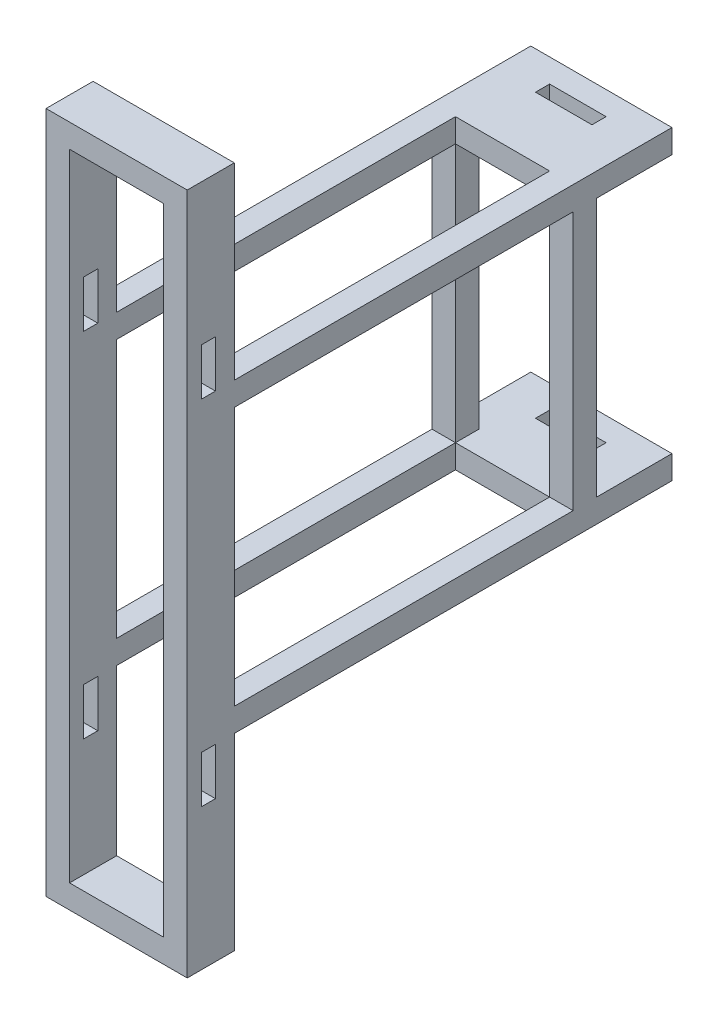
SolidWorks part; units mm, degrees
ref_plane "Front Plane" through (0, 0, 0) normal (0, 0, 1) x (1, 0, 0)
ref_plane "Top Plane" through (0, 0, 0) normal (0, 1, 0) x (1, 0, 0)
ref_plane "Right Plane" through (0, 0, 0) normal (1, 0, 0) x (0, 0, -1)
sketch "Sketch1" plane through (0, 0, 0) normal (0, 1, 0) x (1, 0, 0)
  line L0 (-18.5261, 51.6485) -> (11.4739, 51.6485)
  line L9 (-18.5261, -51.3515) -> (11.4739, -51.3515)
  line L10 (11.4739, -51.3515) -> (11.4739, 51.6485)
  line L11 (-18.5261, 51.6485) -> (-18.5261, -51.3515)
  point P0 (-18.5261, 51.6485)
  point P1 (11.4739, 51.6485)
  point P4 (-18.5261, -51.3515)
  point P5 (11.4739, -51.3515)
  dimension "D1" = 30
  dimension "96" = 103
extrude "Boss-Extrude1" add sketch "Sketch1" along normal blind 5 contours L11 L9 L10 L0
sketch "Sketch2" plane through (0, 5, 0) normal (0, 1, 0) x (1, 0, 0)
  line L0 (-18.5261, 51.6485) -> (-18.5261, -51.3515) construction
  line L1 (-9.5261, 46.6485) -> (2.4739, 46.6485)
  line L2 (-9.5261, 46.6485) -> (-9.5261, 43.6485)
  line L3 (-9.5261, 43.6485) -> (2.4739, 43.6485)
  line L4 (2.4739, 46.6485) -> (2.4739, 43.6485)
  line L5 (11.4739, -51.3515) -> (11.4739, 51.6485) construction
  line L6 (-18.5261, 51.6485) -> (11.4739, 51.6485) construction
  line L9 (6.4739, -51.3515) -> (-13.5261, -51.3515)
  line L10 (6.4739, -51.3515) -> (6.4739, 30.6485)
  line L11 (6.4739, 30.6485) -> (-13.5261, 30.6485)
  line L12 (-13.5261, -51.3515) -> (-13.5261, 30.6485)
  line L17 (-18.5261, -51.3515) -> (11.4739, -51.3515) construction
  dimension "D1" = 9
  dimension "D2" = 9
  dimension "D3" = 5
  dimension "D4" = 3
  dimension "D5" = 13
  dimension "D6" = 5
  dimension "D7" = 5
  dimension "D8" = 0
  dimension "D9" = 12
  dimension "D10" = 82
  dimension "D11" = 20
extrude "Cut-Extrude1" cut sketch "Sketch2" against normal blind 5
sketch "Sketch3" plane through (0, 0, 0) normal (0, -1, 0) x (1, 0, 0)
  line L0 (-13.5261, -30.6485) -> (-13.5261, 51.3515) construction
  line L1 (-18.5261, 51.3515) -> (-13.5261, 51.3515)
  line L2 (-18.5261, 51.3515) -> (-18.5261, 41.3515)
  line L3 (-18.5261, 41.3515) -> (-13.5261, 41.3515)
  line L4 (-13.5261, 51.3515) -> (-13.5261, 41.3515)
  line L5 (-18.5261, -35.6485) -> (-13.5261, -35.6485)
  line L6 (6.4739, 41.3515) -> (11.4739, 41.3515)
  line L7 (6.4739, 41.3515) -> (6.4739, 51.3515)
  line L8 (6.4739, 51.3515) -> (11.4739, 51.3515)
  line L9 (11.4739, 41.3515) -> (11.4739, 51.3515)
  line L10 (11.4739, -35.6485) -> (6.4739, -35.6485)
  line L11 (11.4739, -35.6485) -> (11.4739, -30.6485)
  line L12 (11.4739, -30.6485) -> (6.4739, -30.6485)
  line L13 (6.4739, -35.6485) -> (6.4739, -30.6485)
  line L14 (-18.5261, -35.6485) -> (-18.5261, -30.6485)
  line L15 (-18.5261, -30.6485) -> (-13.5261, -30.6485)
  line L16 (-13.5261, -35.6485) -> (-13.5261, -30.6485)
  line L17 (6.4739, 51.3515) -> (6.4739, -30.6485) construction
  dimension "D1" = 5
  dimension "D2" = 5
  dimension "D3" = 5
  dimension "D4" = 10
  dimension "D5" = 20
  dimension "D6" = 10
extrude "Boss-Extrude2" add sketch "Sketch3" along normal blind 55
sketch "Sketch8" plane through (0, -55, 0) normal (0, -1, 0) x (-1, 0, 0)
  line L3 (18.5261, -51.3515) -> (-11.4739, -51.3515)
  line L4 (18.5261, -51.3515) -> (18.5261, 51.6485)
  line L5 (18.5261, 51.6485) -> (-11.4739, 51.6485)
  line L6 (-11.4739, -51.3515) -> (-11.4739, 51.6485)
  dimension "D1" = 103
  dimension "D2" = 30
extrude "Boss-Extrude6" add sketch "Sketch8" along normal blind 5
sketch "Sketch10" plane through (0, -60, 0) normal (0, -1, 0) x (1, 0, 0)
  line L0 (-18.5261, 51.3515) -> (-18.5261, -51.6485) construction
  line L1 (-13.5261, 51.3515) -> (6.4739, 51.3515)
  line L2 (-13.5261, 51.3515) -> (-13.5261, -30.6485)
  line L3 (2.4739, -46.6485) -> (-9.5261, -46.6485)
  line L4 (2.4739, -46.6485) -> (2.4739, -43.6485)
  line L5 (2.4739, -43.6485) -> (-9.5261, -43.6485)
  line L6 (-9.5261, -46.6485) -> (-9.5261, -43.6485)
  line L7 (-13.5261, -30.6485) -> (6.4739, -30.6485)
  line L8 (6.4739, 51.3515) -> (6.4739, -30.6485)
  line L9 (11.4739, -51.6485) -> (11.4739, 51.3515) construction
  line L10 (-18.5261, -51.6485) -> (11.4739, -51.6485) construction
  line L18 (11.4739, 51.3515) -> (-18.5261, 51.3515) construction
  dimension "D1" = 9
  dimension "D2" = 9
  dimension "D3" = 3
  dimension "D4" = 5
  dimension "D5" = 13
  dimension "D7" = 5
  dimension "D8" = 5
  dimension "D9" = 0
extrude "Cut-Extrude2" cut sketch "Sketch10" against normal blind 5
sketch "Sketch22" plane through (0, 5, 0) normal (0, 1, 0) x (1, 0, 0)
  line L1 (-18.5261, -51.3515) -> (-13.5261, -51.3515)
  line L2 (-18.5261, -51.3515) -> (-18.5261, -41.3515)
  line L3 (-18.5261, -41.3515) -> (-13.5261, -41.3515)
  line L4 (-13.5261, -51.3515) -> (-13.5261, -41.3515)
  line L6 (11.4739, -51.3515) -> (6.4739, -51.3515)
  line L7 (11.4739, -51.3515) -> (11.4739, -41.3515)
  line L8 (11.4739, -41.3515) -> (6.4739, -41.3515)
  line L9 (6.4739, -51.3515) -> (6.4739, -41.3515)
  dimension "D1" = 10
  dimension "D2" = 5
  dimension "D3" = 10
  dimension "D4" = 5
extrude "Boss-Extrude7" add sketch "Sketch22" along normal blind 35
sketch "Sketch23" plane through (0, 40, 0) normal (0, 1, 0) x (1, 0, 0)
  line L2 (-18.5261, -51.3515) -> (11.4739, -51.3515)
  line L3 (-18.5261, -51.3515) -> (-18.5261, -41.3515)
  line L4 (-18.5261, -41.3515) -> (11.4739, -41.3515)
  line L5 (11.4739, -51.3515) -> (11.4739, -41.3515)
  dimension "D1" = 30
  dimension "D2" = 10
extrude "Boss-Extrude8" add sketch "Sketch23" along normal blind 5
sketch "Sketch25" plane through (0, -60, 0) normal (0, -1, 0) x (-1, 0, 0)
  line L2 (18.5261, -51.3515) -> (13.5261, -51.3515)
  line L3 (18.5261, -51.3515) -> (18.5261, -41.3515)
  line L4 (18.5261, -41.3515) -> (13.5261, -41.3515)
  line L5 (13.5261, -51.3515) -> (13.5261, -41.3515)
  line L6 (-11.4739, -51.3515) -> (-6.4739, -51.3515)
  line L7 (-11.4739, -51.3515) -> (-11.4739, -41.3515)
  line L8 (-11.4739, -41.3515) -> (-6.4739, -41.3515)
  line L9 (-6.4739, -51.3515) -> (-6.4739, -41.3515)
extrude "Boss-Extrude9" add sketch "Sketch25" along normal blind 35
sketch "Sketch26" plane through (0, -95, 0) normal (0, -1, 0) x (1, 0, 0)
  line L1 (-18.5261, 51.3515) -> (11.4739, 51.3515)
  line L2 (-18.5261, 51.3515) -> (-18.5261, 41.3515)
  line L3 (-18.5261, 41.3515) -> (11.4739, 41.3515)
  line L4 (11.4739, 51.3515) -> (11.4739, 41.3515)
extrude "Boss-Extrude10" add sketch "Sketch26" along normal blind 5
sketch "Sketch28" plane through (11.4739, 0, 0) normal (1, 0, 0) x (0, 0, -1)
  line L0 (-41.3515, 45) -> (-41.3515, 5) construction
  line L1 (-48.3515, 15) -> (-45.3515, 15)
  line L2 (-48.3515, 15) -> (-48.3515, 5)
  line L3 (-48.3515, 5) -> (-45.3515, 5)
  line L4 (-45.3515, 15) -> (-45.3515, 5)
  line L7 (-41.3515, 5) -> (51.6485, 5) construction
  line L8 (-41.3515, -100) -> (-41.3515, -60) construction
  line L9 (51.6485, -60) -> (-41.3515, -60) construction
  line L11 (-48.3515, -60) -> (-45.3515, -60)
  line L12 (-48.3515, -60) -> (-48.3515, -70)
  line L13 (-48.3515, -70) -> (-45.3515, -70)
  line L14 (-45.3515, -60) -> (-45.3515, -70)
  dimension "D1" = 4
  dimension "3" = 3
  dimension "D2" = 0
  dimension "D3" = 10
  dimension "D4" = 3
  dimension "D5" = 10
  dimension "D6" = 4
  dimension "0" = 0
extrude "Cut-Extrude4" cut sketch "Sketch28" against normal blind 34
